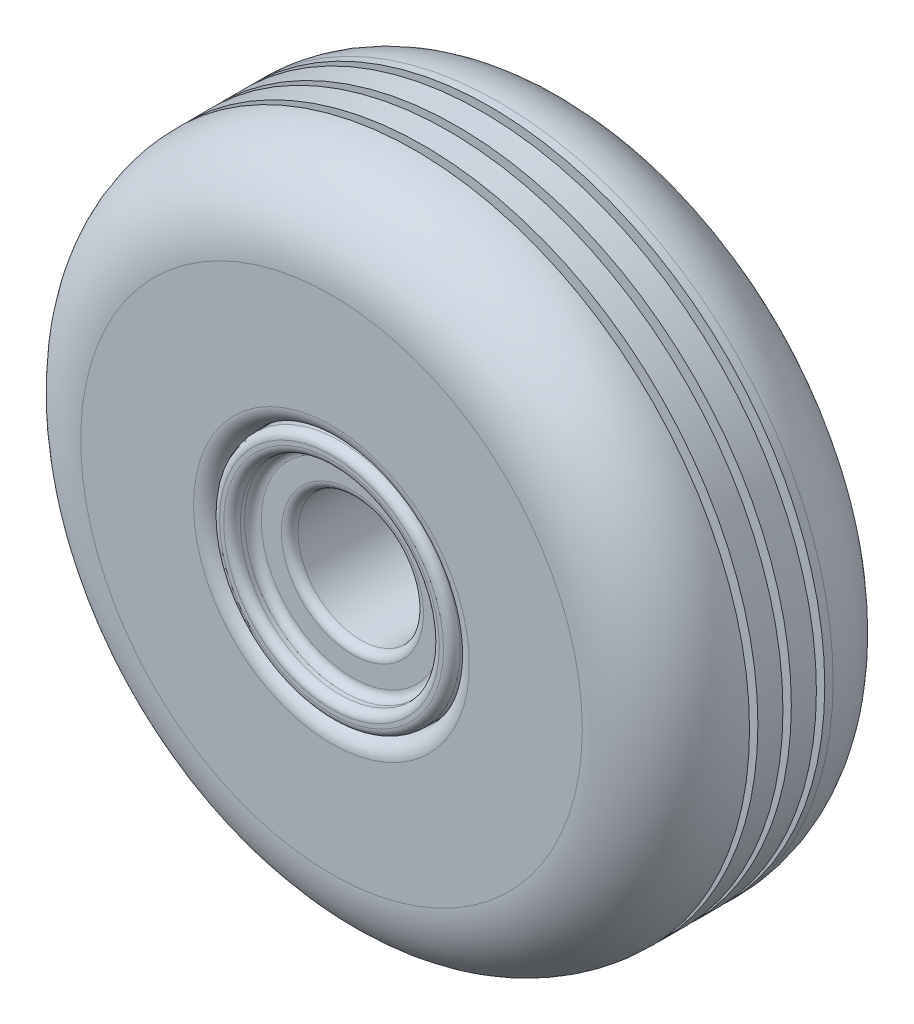
SolidWorks part; units mm, degrees
ref_plane "Front" through (0, 0, 0) normal (0, 0, 1) x (1, 0, 0)
ref_plane "Top" through (0, 0, 0) normal (0, 1, 0) x (1, 0, 0)
ref_plane "Right" through (0, 0, 0) normal (1, 0, 0) x (0, 0, -1)
sketch "Sketch1" plane through (0, 0, 0) normal (1, 0, 0) x (0, 0, -1)
  line L17 (-31.75, 0) -> (31.75, 0) construction
  line L18 (-38.1, -36.576) -> (38.1, -36.576) construction
  line L19 (-38.1, -36.576) -> (-38.1, 36.576) construction
  line L20 (-38.1, 36.576) -> (38.1, 36.576) construction
  line L21 (38.1, -36.576) -> (38.1, 36.576) construction
  line L22 (-38.1, -36.576) -> (38.1, 36.576) construction
  line L23 (-38.1, 36.576) -> (38.1, -36.576) construction
  line L24 (-38.1, 36.576) -> (38.1, 36.576)
  line L30 (-31.75, 30.226) -> (-38.1, 30.226)
  line L31 (-38.1, 30.226) -> (-38.1, 36.576)
  line L35 (31.75, 30.226) -> (38.1, 30.226)
  line L36 (38.1, 30.226) -> (38.1, 36.576)
  line L37 (-31.75, 0) -> (31.75, 0)
  line L38 (-31.75, 30.226) -> (-31.75, 0)
  line L39 (31.75, 0) -> (31.75, 30.226)
  point P0 (0, 0)
  dimension "D1" = 73.152
  dimension "D2" = 76.2
  dimension "D3" = 63.5
  dimension "D4" = 31.75
  dimension "D5" = 6.35
revolve "Revolve1" add sketch "Sketch1" angle 360 about L37
sketch "Sketch2" plane through (0, 0, 0) normal (1, 0, 0) x (0, 0, -1)
  line L1 (-38.1, -101.6) -> (38.1, -101.6) construction
  line L2 (-38.1, -101.6) -> (-38.1, 76.2) construction
  line L4 (38.1, -101.6) -> (38.1, 76.2) construction
  line L5 (-38.1, -101.6) -> (38.1, 101.6) construction
  line L6 (-38.1, 101.6) -> (38.1, -101.6) construction
  line L7 (38.1, 36.576) -> (-38.1, 36.576) construction
  line L8 (0, 36.576) -> (-38.1, 36.576) construction
  line L12 (0, 0) -> (77.6539, 0) construction
  line L13 (-12.7, 101.6) -> (-12.7, 97.184)
  line L14 (-12.7, 97.184) -> (-10.16, 97.184)
  line L15 (-10.16, 97.184) -> (-10.16, 101.6)
  line L16 (-10.16, 101.6) -> (-2.54, 101.6)
  line L17 (-2.54, 101.6) -> (-2.54, 97.184)
  line L18 (-2.54, 97.184) -> (0, 97.184)
  line L19 (0, 97.184) -> (0, 101.6)
  line L20 (0, 101.6) -> (7.62, 101.6)
  line L21 (7.62, 101.6) -> (7.62, 97.184)
  line L22 (7.62, 97.184) -> (10.16, 97.184)
  line L23 (10.16, 97.184) -> (10.16, 101.6)
  line L24 (10.16, 101.6) -> (12.7, 101.6)
  line L25 (-38.1, 76.2) -> (-38.1, 36.83)
  line L26 (-38.1, 36.83) -> (38.1, 36.83)
  line L27 (38.1, 36.83) -> (38.1, 76.2)
  arc A0 (38.1, 76.2) -> (12.7, 101.6) centre (12.7, 76.2) ccw
  arc A1 (-12.7, 101.6) -> (-38.1, 76.2) centre (-12.7, 76.2) ccw
  point P0 (0, 0)
  dimension "D3" = 25.4
  dimension "D1" = 76.2
  dimension "D2" = 203.2
  dimension "D4" = 2.54
  dimension "D5" = 2.54
  dimension "D6" = 2.54
  dimension "D7" = 7.62
  dimension "D8" = 7.62
  dimension "D9" = 0.254
revolve "Revolve2" add sketch "Sketch2" angle 360 about L12
sketch "Sketch3" plane through (0, 0, 0) normal (0, 0, 1) x (1, 0, 0)
  circle A0 centre (0, 0) radius 19.05
  dimension "D1" = 38.1
extrude "Cut-Extrude1" cut sketch "Sketch3" against normal up to next (31.75 mm away) and the other way up to next (31.75 mm away) contours A0
fillet "Fillet1" radius 2.54 8 edges at (30.226, 0, -31.75) (19.05, 0, -31.75) (36.576, 0, -38.1) (30.226, 0, -38.1) (-19.05, 0, 31.75) (30.226, 0, 31.75) (30.226, 0, 38.1) (36.576, 0, 38.1)
fillet "Fillet2" radius 5.08 2 edges at (36.83, 0, -38.1) (36.83, 0, 38.1)
